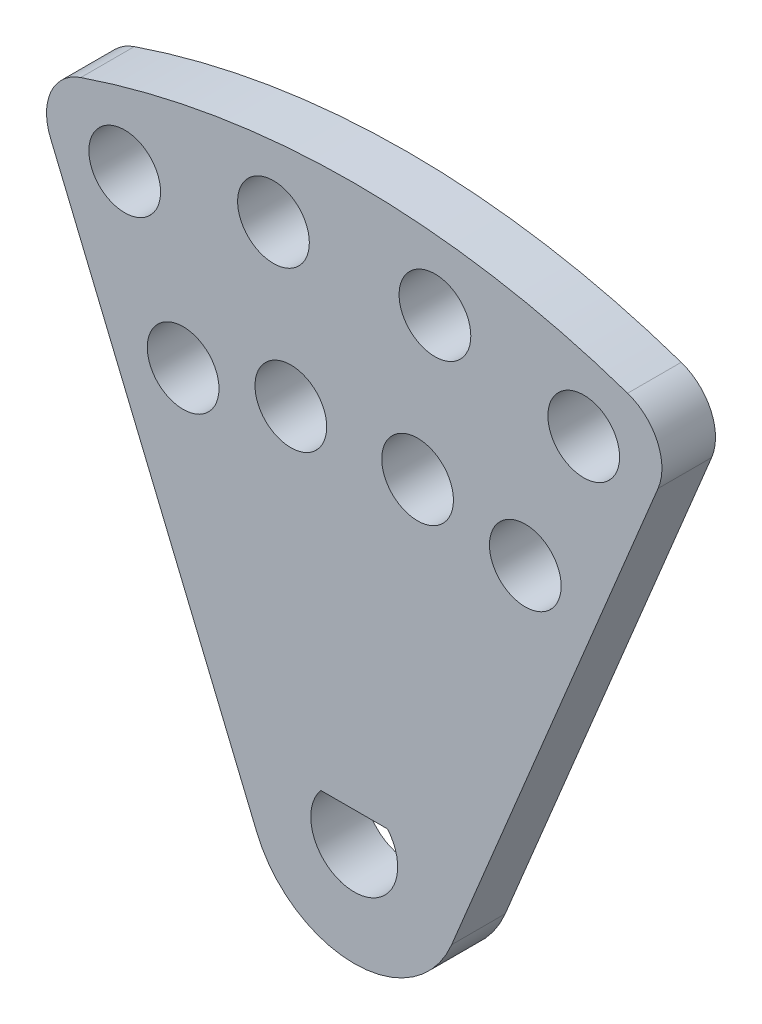
SolidWorks part; units mm, degrees
material "Alumina"
ref_plane "Front Plane" through (0, 0, 0) normal (0, 0, 1) x (1, 0, 0)
ref_plane "Top Plane" through (0, 0, 0) normal (0, 1, 0) x (1, 0, 0)
ref_plane "Right Plane" through (0, 0, 0) normal (1, 0, 0) x (0, 0, -1)
sketch "Sketch2" plane through (0, 0, 0) normal (0, 0, 1) x (1, 0, 0)
  line L0 (-3.9538, 3.3) -> (3.9538, 3.3)
  line L1 (-11.5485, -4.7835) -> (11.5485, -4.7835) construction
  line L2 (11.5485, -4.7835) -> (38.3827, 60)
  line L3 (-11.5485, -4.7835) -> (-38.3827, 60)
  line L4 (-38.3827, 60) -> (38.3827, 60) construction
  line L5 (0, -32.6641) -> (11.5485, -4.7835) construction
  line L6 (0, -32.6641) -> (-11.5485, -4.7835) construction
  arc A0 (-3.9538, 3.3) -> (3.9538, 3.3) centre (0, 0) ccw
  arc A1 (-11.5485, -4.7835) -> (11.5485, -4.7835) centre (0, 0) ccw
  arc A3 (-27.2033, 55.2221) -> (27.2033, 55.2221) centre (0, -32.6641) cw construction
  arc A4 (-38.3827, 60) -> (38.3827, 60) centre (0, -32.6641) cw
  circle A5 centre (-27.2033, 55.2221) radius 4.25
  circle A6 centre (-9.57, 58.8368) radius 4.25
  circle A7 centre (9.57, 58.8368) radius 4.25
  circle A8 centre (27.2033, 55.2221) radius 4.25
  arc A9 (-20.2782, 38.5033) -> (20.2782, 38.5033) centre (0, -32.6641) cw construction
  circle A10 centre (-20.2782, 38.5033) radius 4.25
  circle A11 centre (-7.5112, 40.9537) radius 4.25
  circle A12 centre (7.5112, 40.9537) radius 4.25
  circle A13 centre (20.2782, 38.5033) radius 4.25
  point P0 (0, 0)
  point P5 (0, 10)
  point P11 (0, -32.6641)
  point P14 (-9.57, 58.8368)
  point P15 (9.57, 58.8368)
  point P24 (-7.5112, 40.9537)
  point P25 (7.5112, 40.9537)
  dimension "D1" = 5.15
  dimension "D4" = 12.5
  dimension "D11" = 8.5
  dimension "D12" = 8.5
  dimension "D13" = 8.5
  dimension "D14" = 8.5
  dimension "D15" = 92
  dimension "D21" = 8.5
  dimension "D22" = 8.5
  dimension "D23" = 8.5
  dimension "D24" = 8.5
  dimension "D3" = 10
  dimension "D5" = 45
  dimension "D6" = 60
  dimension "D7" = 8.5
  dimension "D8" = 8.5
  dimension "D9" = 18
  dimension "D10" = 18
  dimension "D16" = 8.5
  dimension "D17" = 8.5
  dimension "D18" = 18
  dimension "D19" = 13
  dimension "D20" = 13
  dimension "D25" = 3.3
extrude "Boss-Extrude1" add sketch "Sketch2" along normal blind 6.35
fillet "Fillet1" radius 6 2 edges at (38.3827, 60, 3.175) (-38.3827, 60, 3.175)
equation "\"motorShaftDiameter\"= 10mm"
equation "\"motorShaftNotchLength\"= 6mm"
equation "\"D1@Sketch2\"=\"motorShaftDiameter\"/2 + 0.15"
equation "\"tieRodHoleDiameter\"= 8.5mm"
equation "\"D7@Sketch2\"=\"tieRodHoleDiameter\""
equation "\"D8@Sketch2\"=\"tieRodHoleDiameter\""
equation "\"plateThickness\"= 25.4 / 4"
equation "\"D1@Boss-Extrude1\"=\"plateThickness\""
equation "\"D11@Sketch2\"=\"tieRodHoleDiameter\""
equation "\"D12@Sketch2\"=\"tieRodHoleDiameter\""
equation "\"D13@Sketch2\"=\"tieRodHoleDiameter\""
equation "\"D14@Sketch2\"=\"tieRodHoleDiameter\""
equation "\"D16@Sketch2\"=\"tieRodHoleDiameter\""
equation "\"D17@Sketch2\"=\"tieRodHoleDiameter\""
equation "\"D21@Sketch2\"=\"tieRodHoleDiameter\""
equation "\"D22@Sketch2\"=\"tieRodHoleDiameter\""
equation "\"D23@Sketch2\"=\"tieRodHoleDiameter\""
equation "\"D24@Sketch2\"=\"tieRodHoleDiameter\""
